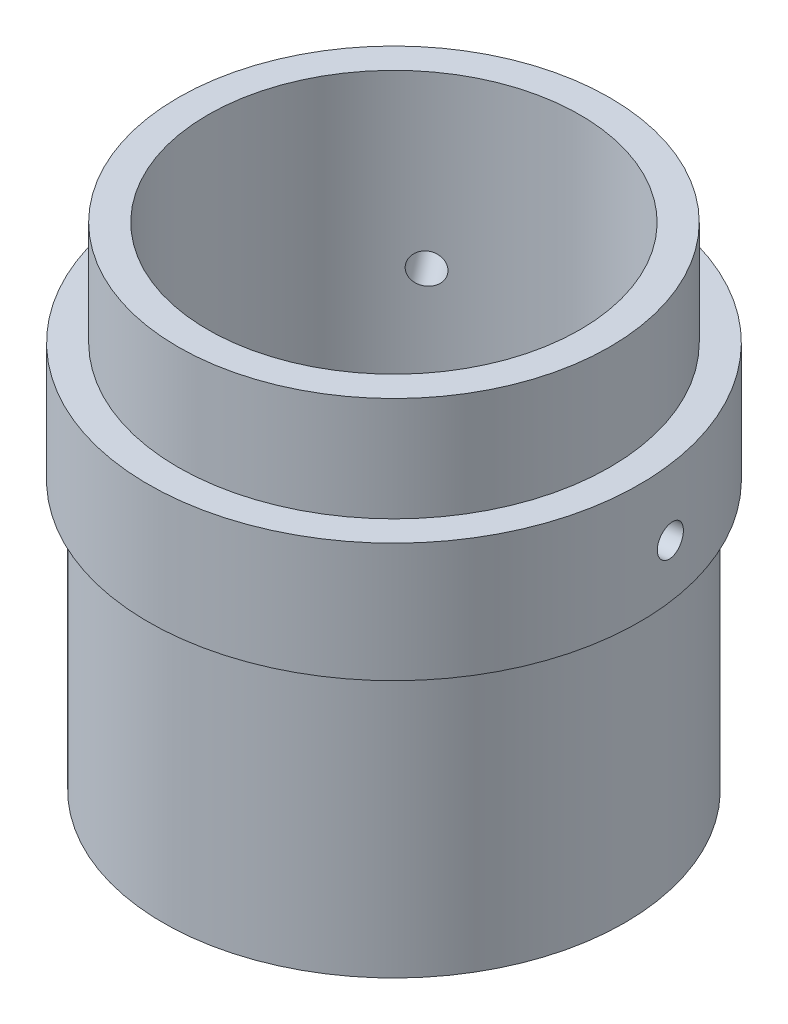
SolidWorks part; units mm, degrees
material "PET"
ref_plane "Alzado" through (0, 0, 0) normal (0, 0, 1) x (1, 0, 0)
ref_plane "Planta" through (0, 0, 0) normal (0, 1, 0) x (1, 0, 0)
ref_plane "Vista lateral" through (0, 0, 0) normal (1, 0, 0) x (0, 0, -1)
sketch "Croquis1" plane through (0, 0, 0) normal (0, 0, 1) x (1, 0, 0)
  line L0 (-9.1288, 76.3736) -> (-9.1288, 0) construction
  line L1 (6.3712, 0) -> (6.3712, 18)
  line L2 (6.3712, 18) -> (7.3712, 18)
  line L3 (7.3712, 18) -> (7.3712, 26)
  line L4 (7.3712, 26) -> (5.3712, 26)
  line L5 (5.3712, 26) -> (5.3712, 33)
  line L6 (5.3712, 33) -> (3.3712, 33)
  line L7 (3.3712, 33) -> (3.3712, 0)
  line L8 (3.3712, 0) -> (6.3712, 0)
  dimension "D1" = 15.5
  dimension "D2" = 18
  dimension "D3" = 8
  dimension "D4" = 16.5
  dimension "D5" = 14.5
  dimension "D6" = 7
  dimension "D7" = 12.5
revolve "Revolución1" add sketch "Croquis1" angle 360 about L0
hole_wizard "Perforador para roscar para macho de roscar para M2.5x0.451" positions "Croquis3D1" profile "Croquis2" hole size "M2.5x0.45" standard "Ansi Metric"
sketch3d "Croquis3D1"
  point P0 (7.2164, 21.5379, -2.2548)
sketch "Croquis2" plane through (7.2164, 21.5379, -2.2548) normal (0, 1, 0) x (-0.1367, 0, -0.9906)
  line L0 (0, 0) -> (0, 10.6159)
  line L1 (0, 10.6159) -> (1.025, 10)
  line L2 (1.025, 10) -> (1.025, 0)
  line L5 (1.025, 0) -> (0, 0)
  line L10 (0, 10.6159) -> (-1.025, 10) construction
  line L11 (0, -6.35) -> (0, 107.95) construction
  dimension "Diámetro de taladro" = 2.05
  dimension "Profundidad de taladro" = 10
  dimension "Ángulo de perforador" = 118
pattern_circular "MatrizC1" count 3 over 360 about axis through (-9.1288, 26, 0) along (0, 1, 0) skipping 2 of "Perforador para roscar para macho de roscar para M2.5x0.451"
